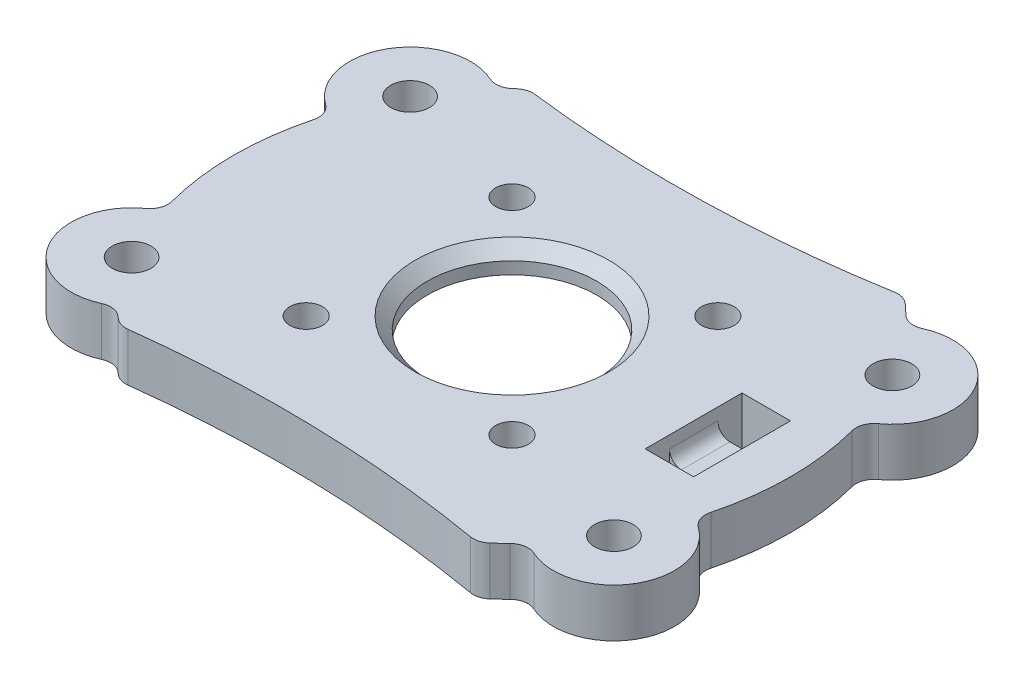
SolidWorks part; units mm, degrees
material "ABS"
ref_plane "前视基准面" through (0, 0, 0) normal (0, 0, 1) x (1, 0, 0)
ref_plane "上视基准面" through (0, 0, 0) normal (0, 1, 0) x (1, 0, 0)
ref_plane "右视基准面" through (0, 0, 0) normal (1, 0, 0) x (0, 0, -1)
sketch "草图1" plane through (0, 0, 0) normal (0, 1, 0) x (1, 0, 0)
  line L1 (-19.9186, -11.5) -> (19.9186, -11.5)
  line L2 (-19.9186, -11.5) -> (-19.9186, 11.5)
  line L3 (-19.9186, 11.5) -> (19.9186, 11.5)
  line L4 (19.9186, -11.5) -> (19.9186, 11.5)
  line L5 (-19.9186, -11.5) -> (19.9186, 11.5) construction
  line L6 (-19.9186, 11.5) -> (19.9186, -11.5) construction
  circle A0 centre (0, 0) radius 23
  circle A1 centre (-19.9186, -11.5) radius 5
  circle A2 centre (19.9186, -11.5) radius 5
  circle A3 centre (19.9186, 11.5) radius 5
  circle A4 centre (-19.9186, 11.5) radius 5
  circle A5 centre (0, 0) radius 13.6
  dimension "D1" = 46
  dimension "D3" = 10
  dimension "D4" = 10
  dimension "D5" = 10
  dimension "D6" = 10
  dimension "D7" = 27.2
  dimension "D2" = 60
extrude "凸台-拉伸1" add sketch "草图1" against normal blind 4 contours A4 A0 A1 L2 | A0 A4 L2 | L2 A4 L3 | L3 A4 A0 | A0 A4 | A5 L3 A3 A0 A4 | A5 L3 A4 L2 A1 L1 | A0 A1 | A0 A1 L1 | L2 A1 A0 | L1 A1 L2 | A0 A3 L3 | A0 A3 | L3 A3 L4 | L4 A3 A0 | A3 L4 A2 A0 | L4 A2 L1 | A0 A2 L4 | A0 A2 | L1 A2 A0 | A5 L1 A1 A0 A2 | A5 L1 A2 L4 A3 L3
sketch "草图2" plane through (0, -4, 0) normal (0, -1, 0) x (1, 0, 0)
  line L1 (19.9186, -11.5) -> (-19.9186, -11.5)
  line L2 (19.9186, -11.5) -> (19.9186, 11.5)
  line L3 (19.9186, 11.5) -> (-19.9186, 11.5)
  line L4 (-19.9186, -11.5) -> (-19.9186, 11.5)
  line L5 (19.9186, -11.5) -> (-19.9186, 11.5) construction
  line L6 (19.9186, 11.5) -> (-19.9186, -11.5) construction
  circle A0 centre (-19.9186, 11.5) radius 1.6
  circle A1 centre (-19.9186, -11.5) radius 1.6
  point P0 (0, 0)
  dimension "D1" = 3.2
  dimension "D2" = 3.2
extrude "切除-拉伸1" cut sketch "草图2" against normal blind 4 contours L3 A0 L4 | L4 A0 L3 | L4 A1 L1 | L1 A1 L4
pattern_circular "阵列(圆周)1" count 2 over 360 about axis through (0, 0, 0) along (0, 1, 0) of "切除-拉伸1"
sketch "草图3" plane through (0, -4, 0) normal (0, -1, 0) x (1, 0, 0)
  arc A0 (42.2289, -26.7852) -> (-36.9716, -22.0861) centre (-2.8082, -116.0694) ccw construction
  arc A1 (42.2289, -26.7852) -> (-36.9716, -22.0861) centre (-2.8082, -116.0694) ccw
  arc A2 (-36.9716, 22.0861) -> (42.2289, 26.7852) centre (-2.8082, 116.0694) ccw construction
  arc A3 (-36.9716, 22.0861) -> (42.2289, 26.7852) centre (-2.8082, 116.0694) ccw
  circle A4 centre (0, 0) radius 23
  arc A8 (21.9331, 6.9238) -> (16.9627, 15.5327) centre (19.9186, 11.5) ccw
  arc A9 (16.9627, 15.5327) -> (-16.9627, 15.5327) centre (0, 0) ccw
  arc A10 (-16.9627, 15.5327) -> (-21.9331, 6.9238) centre (-19.9186, 11.5) ccw
  arc A11 (-21.9331, 6.9238) -> (-21.9331, -6.9238) centre (0, 0) ccw
  arc A12 (-21.9331, -6.9238) -> (-16.9627, -15.5327) centre (-19.9186, -11.5) ccw
  arc A13 (-16.9627, -15.5327) -> (16.9627, -15.5327) centre (0, 0) ccw
  arc A14 (16.9627, -15.5327) -> (21.9331, -6.9238) centre (19.9186, -11.5) ccw
  arc A15 (21.9331, -6.9238) -> (21.9331, 6.9238) centre (0, 0) ccw
  arc A16 (21.9331, 6.9238) -> (16.9627, 15.5327) centre (19.9186, 11.5) ccw
  arc A17 (16.9627, 15.5327) -> (-16.9627, 15.5327) centre (0, 0) ccw
  arc A18 (-16.9627, 15.5327) -> (-21.9331, 6.9238) centre (-19.9186, 11.5) ccw
  arc A19 (-21.9331, 6.9238) -> (-21.9331, -6.9238) centre (0, 0) ccw
  arc A20 (-21.9331, -6.9238) -> (-16.9627, -15.5327) centre (-19.9186, -11.5) ccw
  arc A21 (-16.9627, -15.5327) -> (16.9627, -15.5327) centre (0, 0) ccw
  arc A22 (16.9627, -15.5327) -> (21.9331, -6.9238) centre (19.9186, -11.5) ccw
  arc A23 (21.9331, -6.9238) -> (21.9331, 6.9238) centre (0, 0) ccw
  arc M15 (16.9627, 15.5327) -> (-16.9627, 15.5327) centre (0, 0) ccw
  arc M19 (-16.9627, -15.5327) -> (16.9627, -15.5327) centre (0, 0) ccw
  dimension "D1" = 0
extrude "切除-拉伸2" cut sketch "草图3" against normal blind 10 contours A3 M15 | A1 M19
fillet "圆角1" radius 1.5 12 edges at (-21.9331, -2, 6.9238) (-16.9627, -2, 15.5327) (-16.9627, -2, -15.5327) (-21.9331, -2, -6.9238) (14.7743, -2, -17.6273) (-15.6095, -2, -16.8921) (21.9331, -2, -6.9238) (16.9627, -2, -15.5327) (16.9627, -2, 15.5327) (21.9331, -2, 6.9238) (-15.6095, -2, 16.8921) (14.7743, -2, 17.6273)
sketch "草图4" plane through (0, -4, 0) normal (0, -1, 0) x (1, 0, 0)
  line L0 (-8.1, -4.1473) -> (-8.1, -7.6)
  line L1 (-8.1, 7.6) -> (5.005, 7.6)
  line L2 (-8.1, 7.6) -> (-8.1, 4.1473)
  line L3 (-8.1, -7.6) -> (8.1, -7.6)
  line L4 (8.1, 4.1473) -> (8.1, -7.6)
  line L5 (-8.1, 7.6) -> (8.1, -7.6) construction
  line L6 (-8.1, -7.6) -> (8.1, 7.6) construction
  line L8 (-8.1, 7.6) -> (-8.1, -7.6)
  line L11 (8.1, -7.6) -> (9.1, -7.6)
  line L12 (8.1, -7.6) -> (8.1, 7.6)
  line L13 (8.1, 7.6) -> (9.1, 7.6)
  line L14 (9.1, -7.6) -> (9.1, 7.6)
  circle A0 centre (0, 0) radius 9.1
  circle A1 centre (0, 0) radius 13.6
  circle M34 centre (0, 0) radius 13.6
  dimension "D1" = 18.2
  dimension "D2" = 15.2
  dimension "D3" = 9.1
  dimension "D4" = 17.2
extrude "凸台-拉伸2" add sketch "草图4" against normal up to surface (4 mm away) separate body contours A0 L1 L13 L14 L11 L3 L2 M34 | A0 L2 L3 | L8 A0 | A0 L1 L2 | L1 A0 | L3 A0 | A0 L3 L4 | A0 L4 L11 L14 | A0 L14 L13 L4
combine bodies "组合3" operation type add bodies to combine 110 109
sketch "草图5" plane through (0, -4, 0) normal (0, -1, 0) x (1, 0, 0)
  circle A0 centre (0, 0) radius 12.0708
extrude "凸台-拉伸3" add sketch "草图5" against normal blind 2
sketch "草图6" plane through (0, -2, 0) normal (0, 1, 0) x (1, 0, 0)
  line L0 (0, 6) -> (0, -6)
  circle A0 centre (0, 6) radius 0.9
  circle A1 centre (0, -6) radius 0.9
  dimension "D3" = 1.8
  dimension "D4" = 1.8
  dimension "D1" = 12
  dimension "D2" = 6
extrude "切除-拉伸3" cut sketch "草图6" against normal blind 2
sketch "草图7" plane through (0, -2, 0) normal (0, 1, 0) x (1, 0, 0)
  line L1 (12, -5) -> (-12, -5)
  line L2 (12, -5) -> (12, 5)
  line L3 (12, 5) -> (-12, 5)
  line L4 (-12, -5) -> (-12, 5)
  line L5 (12, -5) -> (-12, 5) construction
  line L6 (12, 5) -> (-12, -5) construction
  circle A0 centre (0, 0) radius 9.1
  point P0 (0, 0)
  arc M9 (5.005, -7.6) -> (5.005, 7.6) centre (0, 0) ccw
  dimension "D1" = 10
  dimension "D2" = 12
extrude "切除-拉伸4" cut sketch "草图7" against normal mid plane 9 contours L2 L3 L1 M9
sketch "草图8" plane through (0, -4, 0) normal (0, -1, 0) x (1, 0, 0)
  line L1 (15, 4) -> (19, 4)
  line L2 (15, 4) -> (15, -4)
  line L3 (15, -4) -> (19, -4)
  line L4 (19, 4) -> (19, -4)
  line L5 (15, 4) -> (19, -4) construction
  line L6 (15, -4) -> (19, 4) construction
  line L7 (15, 2) -> (19, 2)
  line L8 (15, 2) -> (15, -2)
  line L9 (15, -2) -> (19, -2)
  line L10 (19, 2) -> (19, -2)
  line L11 (15, 2) -> (19, -2) construction
  line L12 (15, -2) -> (19, 2) construction
  point P0 (17, 0)
  point P5 (17, 0)
  dimension "D1" = 2
  dimension "D2" = 8
  dimension "D3" = 4
  dimension "D4" = 17
  dimension "D5" = 0
extrude "切除-拉伸5" cut sketch "草图8" against normal blind 22 contours L2 L7 L4 L1 | L9 L2 L3 L4
sketch "草图9" plane through (0, 0, 0) normal (0, 1, 0) x (1, 0, 0)
  line L1 (15, 4) -> (19, 4)
  line L2 (15, 4) -> (15, -4)
  line L3 (15, -4) -> (19, -4)
  line L4 (19, 4) -> (19, -4)
extrude "切除-拉伸6" cut sketch "草图9" against normal blind 2
sketch "草图10" plane through (0, -2, 0) normal (0, 1, 0) x (1, 0, 0)
  line L1 (-9.8093, 4.7625) -> (-6.35, 4.7625)
  line L2 (-9.8093, 4.7625) -> (-9.8093, -4.5729)
  line L3 (-9.8093, -4.5729) -> (-6.35, -4.5729)
  line L4 (-6.35, 4.7625) -> (-6.35, -4.5729)
fillet "圆角2" radius 1 2 edges at (19, -2, 0) (15, -2, 0)
fillet "圆角5" radius 1.5 4 edges at (7.6033, -3, -5) (12, -2, -5) (12, -2, 5) (7.6033, -3, 5)
sketch "草图11" plane through (0, -4, 0) normal (0, -1, 0) x (1, 0, 0)
  line L1 (2.3671, 6) -> (1.1836, 8.05)
  line L2 (1.1836, 8.05) -> (-1.1836, 8.05)
  line L3 (-1.1836, 8.05) -> (-2.3671, 6)
  line L4 (-2.3671, 6) -> (-1.1836, 3.95)
  line L5 (-1.1836, 3.95) -> (1.1836, 3.95)
  line L6 (1.1836, 3.95) -> (2.3671, 6)
  line L7 (2.3671, -6) -> (1.1836, -3.95)
  line L8 (1.1836, -3.95) -> (-1.1836, -3.95)
  line L9 (-1.1836, -3.95) -> (-2.3671, -6)
  line L10 (-2.3671, -6) -> (-1.1836, -8.05)
  line L11 (-1.1836, -8.05) -> (1.1836, -8.05)
  line L12 (1.1836, -8.05) -> (2.3671, -6)
  circle A0 centre (0, 6) radius 2.05 construction
  circle A1 centre (0, -6) radius 2.05 construction
  dimension "D1" = 4.1
  dimension "D2" = 4.1
sketch "草图12" plane through (0, -4, 0) normal (0, -1, 0) x (1, 0, 0)
  circle A0 centre (0, 0) radius 7
  dimension "D1" = 14
extrude "切除-拉伸8" cut sketch "草图12" against normal blind 10
sketch "草图13" plane through (0, -2, 0) normal (0, 1, 0) x (1, 0, 0)
  line L0 (12, -3.5) -> (12, 3.5) construction
  line L1 (12, -3.5) -> (12, 3.5)
  line L5 (-5.005, -7.6) -> (5.005, -7.6)
  line L6 (7.6033, -5) -> (10.0055, -5)
  line L7 (10.0055, 5) -> (7.6033, 5)
  line L8 (5.005, 7.6) -> (-5.005, 7.6)
  line L9 (-8.1, 4.1473) -> (-8.1, -4.1473)
  line L10 (-5.005, -7.6) -> (5.005, -7.6)
  line L11 (7.6033, -5) -> (10.0055, -5)
  line L12 (10.0055, 5) -> (7.6033, 5)
  line L13 (5.005, 7.6) -> (-5.005, 7.6)
  line L14 (-8.1, 4.1473) -> (-8.1, -4.1473)
  arc A0 (10.5, -5) -> (12, -3.5) centre (10.5, -3.5) ccw construction
  arc A1 (12, 3.5) -> (10.5, 5) centre (10.5, 3.5) ccw construction
  arc A2 (10.5, -5) -> (12, -3.5) centre (10.5, -3.5) ccw
  arc A3 (12, 3.5) -> (10.5, 5) centre (10.5, 3.5) ccw
  arc A7 (5.005, -7.6) -> (7.6033, -5) centre (0, 0) ccw
  arc A8 (8.5896, -3.0047) -> (10.0055, -5) centre (10.0055, -3.5) ccw
  arc A9 (8.5896, -3.0047) -> (8.5896, 3.0047) centre (0, 0) ccw
  arc A10 (10.0055, 5) -> (8.5896, 3.0047) centre (10.0055, 3.5) ccw
  arc A11 (7.6033, 5) -> (5.005, 7.6) centre (0, 0) ccw
  arc A12 (-5.005, 7.6) -> (-8.1, 4.1473) centre (0, 0) ccw
  arc A13 (-8.1, -4.1473) -> (-5.005, -7.6) centre (0, 0) ccw
  arc A14 (5.005, -7.6) -> (7.6033, -5) centre (0, 0) ccw
  arc A15 (8.5896, -3.0047) -> (10.0055, -5) centre (10.0055, -3.5) ccw
  arc A16 (8.5896, -3.0047) -> (8.5896, 3.0047) centre (0, 0) ccw
  arc A17 (10.0055, 5) -> (8.5896, 3.0047) centre (10.0055, 3.5) ccw
  arc A18 (7.6033, 5) -> (5.005, 7.6) centre (0, 0) ccw
  arc A19 (-5.005, 7.6) -> (-8.1, 4.1473) centre (0, 0) ccw
  arc A20 (-8.1, -4.1473) -> (-5.005, -7.6) centre (0, 0) ccw
  dimension "D1" = 0
extrude "凸台-拉伸4" add sketch "草图13" along normal up to surface (2 mm away)
sketch "草图14" plane through (0, -4, 0) normal (0, -1, 0) x (1, 0, 0)
  line L0 (10.0055, -5) -> (10.5, -5) construction
  line L1 (12, -3.5) -> (12, 3.5) construction
  line L2 (10.0055, 5) -> (10.5, 5) construction
  line L3 (10.0055, -5) -> (10.5, -5)
  line L4 (12, -3.5) -> (12, 3.5)
  line L5 (10.0055, 5) -> (10.5, 5)
  arc A0 (8.5896, -3.0047) -> (8.5896, 3.0047) centre (0, 0) ccw construction
  arc A1 (8.5896, -3.0047) -> (10.0055, -5) centre (10.0055, -3.5) ccw construction
  arc A2 (10.5, -5) -> (12, -3.5) centre (10.5, -3.5) ccw construction
  arc A3 (12, 3.5) -> (10.5, 5) centre (10.5, 3.5) ccw construction
  arc A4 (10.0055, 5) -> (8.5896, 3.0047) centre (10.0055, 3.5) ccw construction
  arc A5 (8.5896, -3.0047) -> (8.5896, 3.0047) centre (0, 0) ccw
  arc A6 (8.5896, -3.0047) -> (10.0055, -5) centre (10.0055, -3.5) ccw
  arc A7 (10.5, -5) -> (12, -3.5) centre (10.5, -3.5) ccw
  arc A8 (12, 3.5) -> (10.5, 5) centre (10.5, 3.5) ccw
  arc A9 (10.0055, 5) -> (8.5896, 3.0047) centre (10.0055, 3.5) ccw
  arc A24 (-16.175, -16.3514) -> (-16.1424, -16.3836) centre (0, 0) ccw
  arc A25 (-16.1424, -16.3836) -> (-14.9081, -16.8041) centre (-15.0896, -15.3152) ccw
  arc A26 (14.078, -17.5054) -> (-14.9081, -16.8041) centre (-2.8082, -116.0694) ccw
  arc A27 (14.078, -17.5054) -> (15.3312, -17.1451) centre (14.3313, -16.027) ccw
  arc A28 (15.3312, -17.1451) -> (16.175, -16.3514) centre (0, 0) ccw
  arc A29 (17.8503, -16.0522) -> (16.175, -16.3514) centre (17.2299, -17.4178) ccw
  arc A30 (17.8503, -16.0522) -> (22.8268, -7.4328) centre (19.9186, -11.5) ccw
  arc A31 (22.2483, -5.8322) -> (22.8268, -7.4328) centre (23.6992, -6.2126) ccw
  arc A32 (22.2483, -5.8322) -> (22.2483, 5.8322) centre (0, 0) ccw
  arc A33 (22.8268, 7.4328) -> (22.2483, 5.8322) centre (23.6992, 6.2126) ccw
  arc A34 (22.8268, 7.4328) -> (17.8503, 16.0522) centre (19.9186, 11.5) ccw
  arc A35 (16.175, 16.3514) -> (17.8503, 16.0522) centre (17.2299, 17.4178) ccw
  arc A36 (16.175, 16.3514) -> (15.3312, 17.1451) centre (0, 0) ccw
  arc A37 (15.3312, 17.1451) -> (14.078, 17.5054) centre (14.3313, 16.027) ccw
  arc A38 (-14.9081, 16.8041) -> (14.078, 17.5054) centre (-2.8082, 116.0694) ccw
  arc A39 (-14.9081, 16.8041) -> (-16.1424, 16.3836) centre (-15.0896, 15.3152) ccw
  arc A40 (-16.1424, 16.3836) -> (-16.175, 16.3514) centre (0, 0) ccw
  arc A41 (-17.8503, 16.0522) -> (-16.175, 16.3514) centre (-17.2299, 17.4178) ccw
  arc A42 (-17.8503, 16.0522) -> (-22.8268, 7.4328) centre (-19.9186, 11.5) ccw
  arc A43 (-22.2483, 5.8322) -> (-22.8268, 7.4328) centre (-23.6992, 6.2126) ccw
  arc A44 (-22.2483, 5.8322) -> (-22.2483, -5.8322) centre (0, 0) ccw
  arc A45 (-22.8268, -7.4328) -> (-22.2483, -5.8322) centre (-23.6992, -6.2126) ccw
  arc A46 (-22.8268, -7.4328) -> (-17.8503, -16.0522) centre (-19.9186, -11.5) ccw
  arc A47 (-16.175, -16.3514) -> (-17.8503, -16.0522) centre (-17.2299, -17.4178) ccw
  arc A48 (-16.175, -16.3514) -> (-16.1424, -16.3836) centre (0, 0) ccw
  arc A49 (-16.1424, -16.3836) -> (-14.9081, -16.8041) centre (-15.0896, -15.3152) ccw
  arc A50 (14.078, -17.5054) -> (-14.9081, -16.8041) centre (-2.8082, -116.0694) ccw
  arc A51 (14.078, -17.5054) -> (15.3312, -17.1451) centre (14.3313, -16.027) ccw
  arc A52 (15.3312, -17.1451) -> (16.175, -16.3514) centre (0, 0) ccw
  arc A53 (17.8503, -16.0522) -> (16.175, -16.3514) centre (17.2299, -17.4178) ccw
  arc A54 (17.8503, -16.0522) -> (22.8268, -7.4328) centre (19.9186, -11.5) ccw
  arc A55 (22.2483, -5.8322) -> (22.8268, -7.4328) centre (23.6992, -6.2126) ccw
  arc A56 (22.2483, -5.8322) -> (22.2483, 5.8322) centre (0, 0) ccw
  arc A57 (22.8268, 7.4328) -> (22.2483, 5.8322) centre (23.6992, 6.2126) ccw
  arc A58 (22.8268, 7.4328) -> (17.8503, 16.0522) centre (19.9186, 11.5) ccw
  arc A59 (16.175, 16.3514) -> (17.8503, 16.0522) centre (17.2299, 17.4178) ccw
  arc A60 (16.175, 16.3514) -> (15.3312, 17.1451) centre (0, 0) ccw
  arc A61 (15.3312, 17.1451) -> (14.078, 17.5054) centre (14.3313, 16.027) ccw
  arc A62 (-14.9081, 16.8041) -> (14.078, 17.5054) centre (-2.8082, 116.0694) ccw
  arc A63 (-14.9081, 16.8041) -> (-16.1424, 16.3836) centre (-15.0896, 15.3152) ccw
  arc A64 (-16.1424, 16.3836) -> (-16.175, 16.3514) centre (0, 0) ccw
  arc A65 (-17.8503, 16.0522) -> (-16.175, 16.3514) centre (-17.2299, 17.4178) ccw
  arc A66 (-17.8503, 16.0522) -> (-22.8268, 7.4328) centre (-19.9186, 11.5) ccw
  arc A67 (-22.2483, 5.8322) -> (-22.8268, 7.4328) centre (-23.6992, 6.2126) ccw
  arc A68 (-22.2483, 5.8322) -> (-22.2483, -5.8322) centre (0, 0) ccw
  arc A69 (-22.8268, -7.4328) -> (-22.2483, -5.8322) centre (-23.6992, -6.2126) ccw
  arc A70 (-22.8268, -7.4328) -> (-17.8503, -16.0522) centre (-19.9186, -11.5) ccw
  arc A71 (-16.175, -16.3514) -> (-17.8503, -16.0522) centre (-17.2299, -17.4178) ccw
  line M30 (12, 3.5) -> (12, -3.5)
  arc M31 (12, -3.5) -> (10.5, -5) centre (10.5, -3.5) cw
  line M32 (10.5, -5) -> (10.0055, -5)
  arc M33 (10.0055, -5) -> (8.5896, -3.0047) centre (10.0055, -3.5) cw
  arc M34 (8.5896, -3.0047) -> (8.5896, 3.0047) centre (0, 0) ccw
  arc M35 (8.5896, 3.0047) -> (10.0055, 5) centre (10.0055, 3.5) cw
  line M36 (10.0055, 5) -> (10.5, 5)
  arc M37 (10.5, 5) -> (12, 3.5) centre (10.5, 3.5) cw
  dimension "D1" = 0
extrude "凸台-拉伸5" add sketch "草图14" against normal up to surface (4 mm away) contours M30 M37 M36 M35 M34 M33 M32 M31 up to face at (10.2864, 0, 0)
chamfer "倒角1" distance 1 angle 45 1 edges at (0, 0, 7)
sketch "草图15" plane through (0, -4, 0) normal (0, -1, 0) x (1, 0, 0)
  line L1 (-8.5, 8.5) -> (8.5, 8.5)
  line L2 (-8.5, 8.5) -> (-8.5, -8.5)
  line L3 (-8.5, -8.5) -> (8.5, -8.5)
  line L4 (8.5, 8.5) -> (8.5, -8.5)
  line L5 (-8.5, 8.5) -> (8.5, -8.5) construction
  line L6 (-8.5, -8.5) -> (8.5, 8.5) construction
  circle A0 centre (-8.5, -8.5) radius 1.35
  point P0 (0, 0)
  dimension "D3" = 2.7
  dimension "D1" = 17
  dimension "D2" = 17
extrude "切除-拉伸9" cut sketch "草图15" against normal blind 10 contours L2 A0 L3 | L3 A0 L2
pattern_circular "阵列(圆周)2" count 4 over 360 about axis through (0, 0, 0) along (0, 1, 0) of "切除-拉伸9"
sketch "草图16" plane through (0, -4, 0) normal (0, -1, 0) x (1, 0, 0)
  line L1 (11.65, -11.65) -> (-11.65, -11.65)
  line L2 (11.65, -11.65) -> (11.65, 11.65)
  line L3 (11.65, 11.65) -> (-11.65, 11.65)
  line L4 (-11.65, -11.65) -> (-11.65, 11.65)
  line L5 (11.65, -11.65) -> (-11.65, 11.65) construction
  line L6 (11.65, 11.65) -> (-11.65, -11.65) construction
  point P0 (0, 0)
  dimension "D1" = 23.3
  dimension "D2" = 23.3
extrude "切除-拉伸10" cut sketch "草图16" against normal blind 2
fillet "圆角6" radius 2.9 4 edges at (11.65, -3, -11.65) (-11.65, -3, -11.65) (11.65, -3, 11.65) (-11.65, -3, 11.65)
equation "\"1.5.00mm\"=2"
